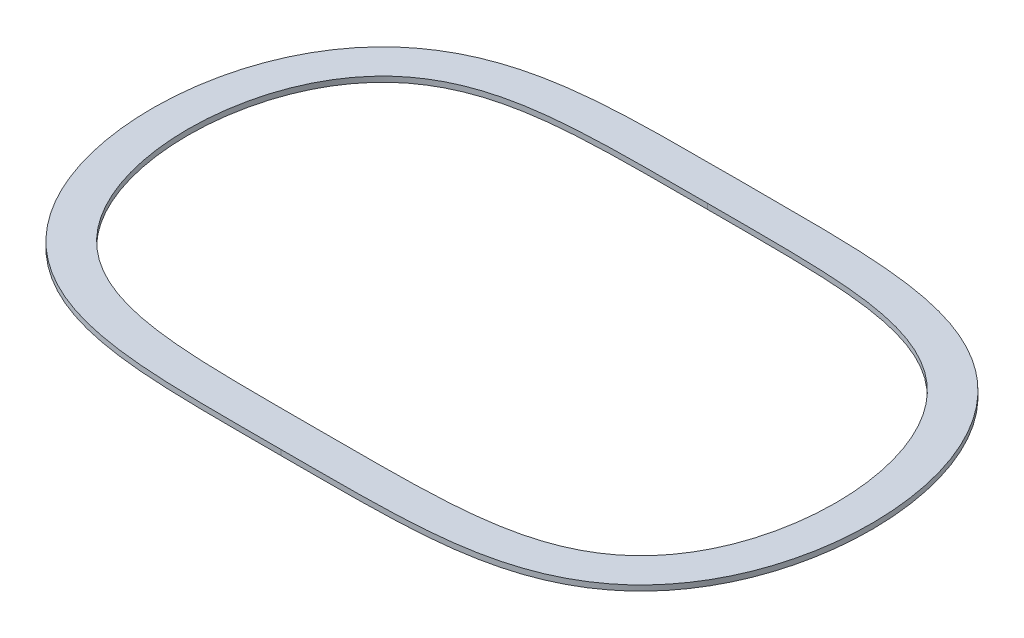
SolidWorks part; units mm, degrees
ref_plane "Front Plane" through (0, 0, 0) normal (0, 0, 1) x (1, 0, 0)
ref_plane "Top Plane" through (0, 0, 0) normal (0, 1, 0) x (1, 0, 0)
ref_plane "Right Plane" through (0, 0, 0) normal (1, 0, 0) x (0, 0, -1)
sketch "Sketch1" plane through (0, 0, 0) normal (0, 1, 0) x (1, 0, 0)
  spline S0 degree 4 poles (0, 129.0994) (4.3298, 129.0999) (12.9895, 129.0995) (25.9763, 129.0992) (43.2902, 129.014) (60.6007, 128.6712) (77.8947, 127.8129) (95.543, 126.046) (113.014, 122.896) (130.0464, 117.7971) (146.1581, 110.2269) (160.4313, 100.265) (172.6933, 87.9119) (182.6634, 73.6634) (190.3404, 58.0791) (195.8654, 41.6227) (199.4008, 24.6362) (201.0699, 7.3707) (200.9352, -9.9735) (198.9912, -27.2107) (195.1663, -44.1354) (189.3287, -60.4854) (181.3147, -75.9018) (170.9944, -89.9023) (157.8662, -102.4377) (141.9679, -112.6829) (124.642, -119.7567) (106.7084, -124.2192) (88.4462, -126.9034) (70.0513, -128.3227) (45.6298, -129.0998) (25.3491, -129.0993) (10.1399, -129.0994) (0, -129.0994) knots 0 0 0 0 0 0.03122 0.06244 0.093642 0.124843 0.156053 0.187263 0.221451 0.252662 0.283872 0.315082 0.346292 0.377502 0.408713 0.439923 0.471133 0.502344 0.533554 0.564765 0.595975 0.627185 0.658396 0.689606 0.720816 0.757371 0.793926 0.823852 0.853778 0.890332 0.926886 1 1 1 1 1 construction
  spline S1 degree 4 poles (0, 129.0994) (4.3298, 129.0999) (12.9895, 129.0995) (25.9763, 129.0992) (43.2902, 129.014) (60.6007, 128.6712) (77.8947, 127.8129) (95.543, 126.046) (113.014, 122.896) (130.0464, 117.7971) (146.1581, 110.2269) (160.4313, 100.265) (172.6933, 87.9119) (182.6634, 73.6634) (190.3404, 58.0791) (195.8654, 41.6227) (199.4008, 24.6362) (201.0699, 7.3707) (200.9352, -9.9735) (198.9912, -27.2107) (195.1663, -44.1354) (189.3287, -60.4854) (181.3147, -75.9018) (170.9944, -89.9023) (157.8662, -102.4377) (141.9679, -112.6829) (124.642, -119.7567) (106.7084, -124.2192) (88.4462, -126.9034) (70.0513, -128.3227) (45.6298, -129.0998) (25.3491, -129.0993) (10.1399, -129.0994) (0, -129.0994) knots 0 0 0 0 0 0.03122 0.06244 0.093642 0.124843 0.156053 0.187263 0.221451 0.252662 0.283872 0.315082 0.346292 0.377502 0.408713 0.439923 0.471133 0.502344 0.533554 0.564765 0.595975 0.627185 0.658396 0.689606 0.720816 0.757371 0.793926 0.823852 0.853778 0.890332 0.926886 1 1 1 1 1
  spline S2 degree 4 poles (0, 129.0994) (-4.3298, 129.0999) (-12.9895, 129.0995) (-25.9763, 129.0992) (-43.2902, 129.014) (-60.6007, 128.6712) (-77.8947, 127.8129) (-95.543, 126.046) (-113.014, 122.896) (-130.0464, 117.7971) (-146.1581, 110.2269) (-160.4313, 100.265) (-172.6933, 87.9119) (-182.6634, 73.6634) (-190.3404, 58.0791) (-195.8654, 41.6227) (-199.4008, 24.6362) (-201.07, 7.3707) (-200.9352, -9.9735) (-198.9912, -27.2107) (-195.1663, -44.1354) (-189.3287, -60.4854) (-181.3147, -75.9018) (-170.9944, -89.9023) (-157.8662, -102.4377) (-141.9679, -112.6829) (-124.642, -119.7567) (-106.7084, -124.2192) (-88.4462, -126.9034) (-70.0513, -128.3227) (-45.6298, -129.0998) (-25.3491, -129.0993) (-10.1399, -129.0994) (0, -129.0994) knots 0 0 0 0 0 0.03122 0.06244 0.093642 0.124843 0.156053 0.187263 0.221451 0.252662 0.283872 0.315082 0.346292 0.377502 0.408713 0.439923 0.471133 0.502344 0.533554 0.564765 0.595975 0.627185 0.658396 0.689606 0.720816 0.757371 0.793926 0.823852 0.853778 0.890332 0.926886 1 1 1 1 1 construction
  spline S3 degree 4 poles (0, 129.0994) (-4.3298, 129.0999) (-12.9895, 129.0995) (-25.9763, 129.0992) (-43.2902, 129.014) (-60.6007, 128.6712) (-77.8947, 127.8129) (-95.543, 126.046) (-113.014, 122.896) (-130.0464, 117.7971) (-146.1581, 110.2269) (-160.4313, 100.265) (-172.6933, 87.9119) (-182.6634, 73.6634) (-190.3404, 58.0791) (-195.8654, 41.6227) (-199.4008, 24.6362) (-201.07, 7.3707) (-200.9352, -9.9735) (-198.9912, -27.2107) (-195.1663, -44.1354) (-189.3287, -60.4854) (-181.3147, -75.9018) (-170.9944, -89.9023) (-157.8662, -102.4377) (-141.9679, -112.6829) (-124.642, -119.7567) (-106.7084, -124.2192) (-88.4462, -126.9034) (-70.0513, -128.3227) (-45.6298, -129.0998) (-25.3491, -129.0993) (-10.1399, -129.0994) (0, -129.0994) knots 0 0 0 0 0 0.03122 0.06244 0.093642 0.124843 0.156053 0.187263 0.221451 0.252662 0.283872 0.315082 0.346292 0.377502 0.408713 0.439923 0.471133 0.502344 0.533554 0.564765 0.595975 0.627185 0.658396 0.689606 0.720816 0.757371 0.793926 0.823852 0.853778 0.890332 0.926886 1 1 1 1 1
extrude "body" add sketch "Sketch1" along normal blind 3 contours S1 S3
sketch "Sketch6" plane through (0, 3, 0) normal (0, 1, 0) x (1, 0, 0)
  spline S5 degree 3 poles (-1189.8471, -2691.9776) (-851.3039, -83.2854) (-417.4901, -109.3473) (20.4963, -109.0943) (25.6202, -109.0876) (35.8668, -109.04) (40.9894, -108.999) (51.2318, -108.8361) (56.3515, -108.7144) (66.5856, -108.3212) (71.6999, -108.05) (81.9197, -107.2612) (87.0251, -106.7439) (94.6729, -105.6809) (97.2204, -105.2781) (102.2772, -104.3607) (104.7904, -103.8456) (112.2751, -102.0992) (117.1924, -100.6679) (123.2134, -98.4163) (124.4113, -97.9427) (126.7933, -96.9452) (127.9778, -96.4209) (131.4785, -94.7812) (133.7523, -93.595) (140.3811, -89.7379) (144.5435, -86.7682) (149.392, -82.5065) (150.3459, -81.6248) (152.1979, -79.8258) (153.0985, -78.9066) (155.7261, -76.0919) (157.3793, -74.1393) (160.501, -70.0915) (161.9697, -67.9965) (164.0427, -64.7536) (164.712, -63.6559) (166.0083, -61.4278) (166.6366, -60.2949) (169.6536, -54.5915) (171.681, -49.8966) (175.1017, -40.2896) (176.4941, -35.3774) (177.8785, -29.1151) (178.1374, -27.8565) (178.62, -25.3272) (178.8436, -24.0558) (179.4585, -20.2467) (179.7955, -17.7068) (180.5991, -10.0856) (180.8599, -5.0028) (180.8542, 5.1665) (180.5877, 10.2531) (179.7733, 17.8859) (179.4324, 20.4307) (178.6032, 25.5213) (178.1186, 28.0448) (176.4496, 35.5446) (175.0517, 40.4525) (172.4735, 47.659) (171.5333, 50.0351) (169.9905, 53.5565) (169.4541, 54.7232) (168.3345, 57.0414) (167.7501, 58.1952) (164.7187, 63.8967) (161.963, 68.2131) (157.2694, 74.2728) (155.611, 76.2232) (152.9725, 79.037) (152.0678, 79.9562) (150.2061, 81.756) (149.2536, 82.6319) (144.4099, 86.8689) (140.2492, 89.8259) (133.6164, 93.6684) (131.3403, 94.8505) (127.8345, 96.4851) (126.6487, 97.0077) (124.2685, 98.0001) (123.0721, 98.4711) (117.0607, 100.7095) (112.1585, 102.1297) (102.2213, 104.4416) (97.1861, 105.3322) (89.5636, 106.3908) (87.0089, 106.6973) (81.9021, 107.2316) (79.3476, 107.4598) (71.6813, 108.0512) (66.5669, 108.3221) (56.3338, 108.7149) (51.215, 108.8365) (40.9752, 108.9991) (35.8541, 109.04) (25.611, 109.0876) (20.4889, 109.0942) (-449.4968, 109.3759) (-915.1983, 80.7397) (-1306.6879, 2612.612) knots -2.608657 -2.608657 -2.608657 -2.608657 0.03125 0.03125 0.0625 0.0625 0.09375 0.09375 0.125 0.125 0.15625 0.15625 0.1875 0.1875 0.203125 0.203125 0.21875 0.21875 0.25 0.25 0.257812 0.257812 0.265625 0.265625 0.28125 0.28125 0.3125 0.3125 0.320312 0.320312 0.328125 0.328125 0.34375 0.34375 0.359375 0.359375 0.367187 0.367187 0.375 0.375 0.40625 0.40625 0.4375 0.4375 0.445312 0.445312 0.453125 0.453125 0.46875 0.46875 0.5 0.5 0.53125 0.53125 0.546875 0.546875 0.5625 0.5625 0.59375 0.59375 0.609375 0.609375 0.617188 0.617188 0.625 0.625 0.65625 0.65625 0.671875 0.671875 0.679688 0.679688 0.6875 0.6875 0.71875 0.71875 0.734375 0.734375 0.742188 0.742188 0.75 0.75 0.78125 0.78125 0.8125 0.8125 0.828125 0.828125 0.84375 0.84375 0.875 0.875 0.90625 0.90625 0.9375 0.9375 0.96875 0.96875 3.804846 3.804846 3.804846 3.804846 only from (0, -109.0994) to (0, 109.0994)
  spline S6 degree 3 poles (1289.5228, 2619.8445) (916.1228, 80.6753) (449.8512, 109.3764) (-20.4963, 109.0942) (-25.6201, 109.0876) (-35.8667, 109.0399) (-40.9893, 108.999) (-51.2316, 108.8362) (-56.3513, 108.7144) (-66.5853, 108.3212) (-71.6997, 108.0501) (-81.9194, 107.2612) (-87.0248, 106.7439) (-94.6725, 105.681) (-97.22, 105.2783) (-102.2769, 104.3609) (-104.79, 103.8457) (-112.2746, 102.099) (-117.1921, 100.6684) (-123.2129, 98.4166) (-124.4107, 97.9429) (-126.7927, 96.9452) (-127.9772, 96.4209) (-131.478, 94.7813) (-133.7519, 93.5952) (-140.381, 89.7383) (-144.5431, 86.7682) (-149.3918, 82.5067) (-150.3456, 81.6251) (-152.1978, 79.826) (-153.0983, 78.9068) (-155.7259, 76.092) (-159.0324, 72.1868) (-161.9696, 67.9967) (-164.0426, 64.7537) (-164.7119, 63.656) (-166.0082, 61.4279) (-166.6365, 60.2951) (-169.6536, 54.5916) (-171.6809, 49.8966) (-175.1017, 40.2897) (-176.494, 35.3774) (-177.8785, 29.1153) (-178.1374, 27.8567) (-178.6199, 25.3274) (-178.8436, 24.056) (-179.4585, 20.2469) (-179.7955, 17.7069) (-180.5991, 10.0857) (-180.8599, 5.0029) (-180.8542, -5.1665) (-180.5877, -10.253) (-179.7733, -17.8857) (-179.4324, -20.4305) (-178.6033, -25.521) (-178.1187, -28.0446) (-176.4497, -35.5445) (-175.0517, -40.4524) (-172.4735, -47.6589) (-171.5333, -50.0351) (-169.9905, -53.5564) (-169.4541, -54.7231) (-168.3345, -57.0413) (-167.7502, -58.195) (-164.7188, -63.8967) (-161.963, -68.213) (-157.2695, -74.2727) (-155.6112, -76.2231) (-152.9727, -79.0368) (-152.068, -79.9561) (-150.2063, -81.7558) (-149.2538, -82.6318) (-144.4102, -86.8689) (-140.2492, -89.8255) (-133.6166, -93.6682) (-131.3406, -94.8505) (-127.835, -96.4852) (-126.6491, -97.0077) (-124.2689, -98) (-123.0724, -98.4708) (-117.0609, -100.7091) (-112.1589, -102.1299) (-102.2216, -104.4413) (-97.1864, -105.332) (-89.5639, -106.3908) (-87.0092, -106.6973) (-81.9024, -107.2317) (-79.3479, -107.4599) (-71.6816, -108.0512) (-66.5671, -108.3221) (-56.334, -108.7149) (-51.2152, -108.8365) (-40.9754, -108.9991) (-35.8543, -109.0401) (-25.6111, -109.0876) (-20.489, -109.0943) (417.1654, -109.3468) (850.4583, -83.3437) (1207.6066, -2685.0856) knots -2.80603 -2.80603 -2.80603 -2.80603 0.03125 0.03125 0.0625 0.0625 0.09375 0.09375 0.125 0.125 0.15625 0.15625 0.1875 0.1875 0.203125 0.203125 0.21875 0.21875 0.25 0.25 0.257813 0.257813 0.265625 0.265625 0.28125 0.28125 0.3125 0.3125 0.320313 0.320313 0.328125 0.328125 0.34375 0.359375 0.359375 0.367188 0.367188 0.375 0.375 0.40625 0.40625 0.4375 0.4375 0.445313 0.445313 0.453125 0.453125 0.46875 0.46875 0.5 0.5 0.53125 0.53125 0.546875 0.546875 0.5625 0.5625 0.59375 0.59375 0.609375 0.609375 0.617188 0.617188 0.625 0.625 0.65625 0.65625 0.671875 0.671875 0.679688 0.679688 0.6875 0.6875 0.71875 0.71875 0.734375 0.734375 0.742188 0.742188 0.75 0.75 0.78125 0.78125 0.8125 0.8125 0.828125 0.828125 0.84375 0.84375 0.875 0.875 0.90625 0.90625 0.9375 0.9375 0.96875 0.96875 3.607585 3.607585 3.607585 3.607585 only from (0, 109.0994) to (0, -109.0994)
  spline S7 degree 3 poles (0, -109.0994) (5.1241, -109.0994) (10.2483, -109.1002) (20.4963, -109.0943) (25.6202, -109.0876) (35.8668, -109.04) (40.9894, -108.999) (51.2318, -108.8361) (56.3515, -108.7144) (66.5856, -108.3212) (71.6999, -108.05) (81.9197, -107.2612) (87.0251, -106.7439) (94.6729, -105.6809) (97.2204, -105.2781) (102.2772, -104.3607) (104.7904, -103.8456) (112.2751, -102.0992) (117.1924, -100.6679) (123.2134, -98.4163) (124.4113, -97.9427) (126.7933, -96.9452) (127.9778, -96.4209) (131.4785, -94.7812) (133.7523, -93.595) (140.3811, -89.7379) (144.5435, -86.7682) (149.392, -82.5065) (150.3459, -81.6248) (152.1979, -79.8258) (153.0985, -78.9066) (155.7261, -76.0919) (157.3793, -74.1393) (160.501, -70.0915) (161.9697, -67.9965) (164.0427, -64.7536) (164.712, -63.6559) (166.0083, -61.4278) (166.6366, -60.2949) (169.6536, -54.5915) (171.681, -49.8966) (175.1017, -40.2896) (176.4941, -35.3774) (177.8785, -29.1151) (178.1374, -27.8565) (178.62, -25.3272) (178.8436, -24.0558) (179.4585, -20.2467) (179.7955, -17.7068) (180.5991, -10.0856) (180.8599, -5.0028) (180.8542, 5.1665) (180.5877, 10.2531) (179.7733, 17.8859) (179.4324, 20.4307) (178.6032, 25.5213) (178.1186, 28.0448) (176.4496, 35.5446) (175.0517, 40.4525) (172.4735, 47.659) (171.5333, 50.0351) (169.9905, 53.5565) (169.4541, 54.7232) (168.3345, 57.0414) (167.7501, 58.1952) (164.7187, 63.8967) (161.963, 68.2131) (157.2694, 74.2728) (155.611, 76.2232) (152.9725, 79.037) (152.0678, 79.9562) (150.2061, 81.756) (149.2536, 82.6319) (144.4099, 86.8689) (140.2492, 89.8259) (133.6164, 93.6684) (131.3403, 94.8505) (127.8345, 96.4851) (126.6487, 97.0077) (124.2685, 98.0001) (123.0721, 98.4711) (117.0607, 100.7095) (112.1585, 102.1297) (102.2213, 104.4416) (97.1861, 105.3322) (89.5636, 106.3908) (87.0089, 106.6973) (81.9021, 107.2316) (79.3476, 107.4598) (71.6813, 108.0512) (66.5669, 108.3221) (56.3338, 108.7149) (51.215, 108.8365) (40.9752, 108.9991) (35.8541, 109.04) (25.611, 109.0876) (20.4889, 109.0942) (10.2446, 109.1004) (5.1223, 109.0999) (0, 109.0994) knots 0 0 0 0 0.03125 0.03125 0.0625 0.0625 0.09375 0.09375 0.125 0.125 0.15625 0.15625 0.1875 0.1875 0.203125 0.203125 0.21875 0.21875 0.25 0.25 0.257812 0.257812 0.265625 0.265625 0.28125 0.28125 0.3125 0.3125 0.320312 0.320312 0.328125 0.328125 0.34375 0.34375 0.359375 0.359375 0.367187 0.367187 0.375 0.375 0.40625 0.40625 0.4375 0.4375 0.445312 0.445312 0.453125 0.453125 0.46875 0.46875 0.5 0.5 0.53125 0.53125 0.546875 0.546875 0.5625 0.5625 0.59375 0.59375 0.609375 0.609375 0.617188 0.617188 0.625 0.625 0.65625 0.65625 0.671875 0.671875 0.679688 0.679688 0.6875 0.6875 0.71875 0.71875 0.734375 0.734375 0.742188 0.742188 0.75 0.75 0.78125 0.78125 0.8125 0.8125 0.828125 0.828125 0.84375 0.84375 0.875 0.875 0.90625 0.90625 0.9375 0.9375 0.96875 0.96875 1 1 1 1
  spline S8 degree 3 poles (0, 109.0994) (-5.1241, 109.0999) (-10.2483, 109.1004) (-20.4963, 109.0942) (-25.6201, 109.0876) (-35.8667, 109.0399) (-40.9893, 108.999) (-51.2316, 108.8362) (-56.3513, 108.7144) (-66.5853, 108.3212) (-71.6997, 108.0501) (-81.9194, 107.2612) (-87.0248, 106.7439) (-94.6725, 105.681) (-97.22, 105.2783) (-102.2769, 104.3609) (-104.79, 103.8457) (-112.2746, 102.099) (-117.1921, 100.6684) (-123.2129, 98.4166) (-124.4107, 97.9429) (-126.7927, 96.9452) (-127.9772, 96.4209) (-131.478, 94.7813) (-133.7519, 93.5952) (-140.381, 89.7383) (-144.5431, 86.7682) (-149.3918, 82.5067) (-150.3456, 81.6251) (-152.1978, 79.826) (-153.0983, 78.9068) (-155.7259, 76.092) (-159.0324, 72.1868) (-161.9696, 67.9967) (-164.0426, 64.7537) (-164.7119, 63.656) (-166.0082, 61.4279) (-166.6365, 60.2951) (-169.6536, 54.5916) (-171.6809, 49.8966) (-175.1017, 40.2897) (-176.494, 35.3774) (-177.8785, 29.1153) (-178.1374, 27.8567) (-178.6199, 25.3274) (-178.8436, 24.056) (-179.4585, 20.2469) (-179.7955, 17.7069) (-180.5991, 10.0857) (-180.8599, 5.0029) (-180.8542, -5.1665) (-180.5877, -10.253) (-179.7733, -17.8857) (-179.4324, -20.4305) (-178.6033, -25.521) (-178.1187, -28.0446) (-176.4497, -35.5445) (-175.0517, -40.4524) (-172.4735, -47.6589) (-171.5333, -50.0351) (-169.9905, -53.5564) (-169.4541, -54.7231) (-168.3345, -57.0413) (-167.7502, -58.195) (-164.7188, -63.8967) (-161.963, -68.213) (-157.2695, -74.2727) (-155.6112, -76.2231) (-152.9727, -79.0368) (-152.068, -79.9561) (-150.2063, -81.7558) (-149.2538, -82.6318) (-144.4102, -86.8689) (-140.2492, -89.8255) (-133.6166, -93.6682) (-131.3406, -94.8505) (-127.835, -96.4852) (-126.6491, -97.0077) (-124.2689, -98) (-123.0724, -98.4708) (-117.0609, -100.7091) (-112.1589, -102.1299) (-102.2216, -104.4413) (-97.1864, -105.332) (-89.5639, -106.3908) (-87.0092, -106.6973) (-81.9024, -107.2317) (-79.3479, -107.4599) (-71.6816, -108.0512) (-66.5671, -108.3221) (-56.334, -108.7149) (-51.2152, -108.8365) (-40.9754, -108.9991) (-35.8543, -109.0401) (-25.6111, -109.0876) (-20.489, -109.0943) (-10.2446, -109.1002) (-5.1223, -109.0994) (0, -109.0994) knots 0 0 0 0 0.03125 0.03125 0.0625 0.0625 0.09375 0.09375 0.125 0.125 0.15625 0.15625 0.1875 0.1875 0.203125 0.203125 0.21875 0.21875 0.25 0.25 0.257813 0.257813 0.265625 0.265625 0.28125 0.28125 0.3125 0.3125 0.320313 0.320313 0.328125 0.328125 0.34375 0.359375 0.359375 0.367188 0.367188 0.375 0.375 0.40625 0.40625 0.4375 0.4375 0.445313 0.445313 0.453125 0.453125 0.46875 0.46875 0.5 0.5 0.53125 0.53125 0.546875 0.546875 0.5625 0.5625 0.59375 0.59375 0.609375 0.609375 0.617188 0.617188 0.625 0.625 0.65625 0.65625 0.671875 0.671875 0.679688 0.679688 0.6875 0.6875 0.71875 0.71875 0.734375 0.734375 0.742188 0.742188 0.75 0.75 0.78125 0.78125 0.8125 0.8125 0.828125 0.828125 0.84375 0.84375 0.875 0.875 0.90625 0.90625 0.9375 0.9375 0.96875 0.96875 1 1 1 1
  dimension "D1" = 20
extrude "cut-inside" cut sketch "Sketch6" against normal blind 50
